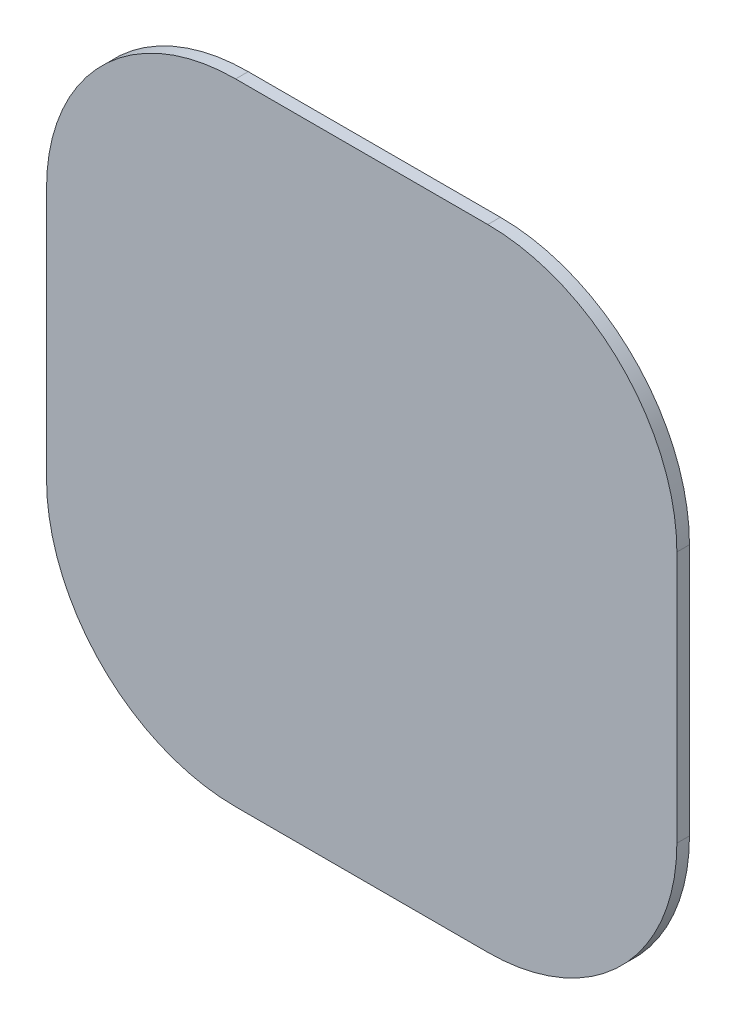
SolidWorks part; units mm, degrees
ref_plane "Front Plane" through (0, 0, 0) normal (0, 0, 1) x (1, 0, 0)
ref_plane "Top Plane" through (0, 0, 0) normal (0, 1, 0) x (1, 0, 0)
ref_plane "Right Plane" through (0, 0, 0) normal (1, 0, 0) x (0, 0, -1)
sketch "Sketch1" plane through (0, 0, 0) normal (0, 0, 1) x (1, 0, 0)
  line L0 (0, 53.5) -> (0, -96.5) construction
  line L1 (-75, 53.5) -> (75, 53.5) construction
  line L2 (-75, 53.5) -> (-75, -96.5) construction
  line L3 (-75, -96.5) -> (75, -96.5) construction
  line L4 (75, 53.5) -> (75, -96.5) construction
  line L5 (-30, 53.5) -> (30, 53.5)
  line L6 (-30, -96.5) -> (30, -96.5) construction
  line L7 (-75, 8.5) -> (75, 8.5) construction
  line L8 (-75, 8.5) -> (-75, -51.5)
  line L9 (-75, -51.5) -> (75, -51.5) construction
  line L10 (75, 8.5) -> (75, -51.5)
  line L11 (-30, -96.5) -> (-0.5, -96.5)
  line L12 (0.5, -96.5) -> (30, -96.5)
  line L13 (-0.5, -96.5) -> (0.5, -96.5)
  arc A0 (-75, 8.5) -> (-30, 53.5) centre (-30, 8.5) cw
  arc A1 (30, 53.5) -> (75, 8.5) centre (30, 8.5) cw
  arc A2 (-75, -51.5) -> (-30, -96.5) centre (-30, -51.5) ccw
  arc A3 (30, -96.5) -> (75, -51.5) centre (30, -51.5) ccw
  point P6 (0, -21.5)
  point P10 (0, 53.5)
  point P19 (0, -96.5)
  dimension "D3" = 45
  dimension "D4" = 45
  dimension "D1" = 150
  dimension "D2" = 150
  dimension "D5" = 53.5
extrude "Boss-Extrude1" add sketch "Sketch1" along normal blind 3
